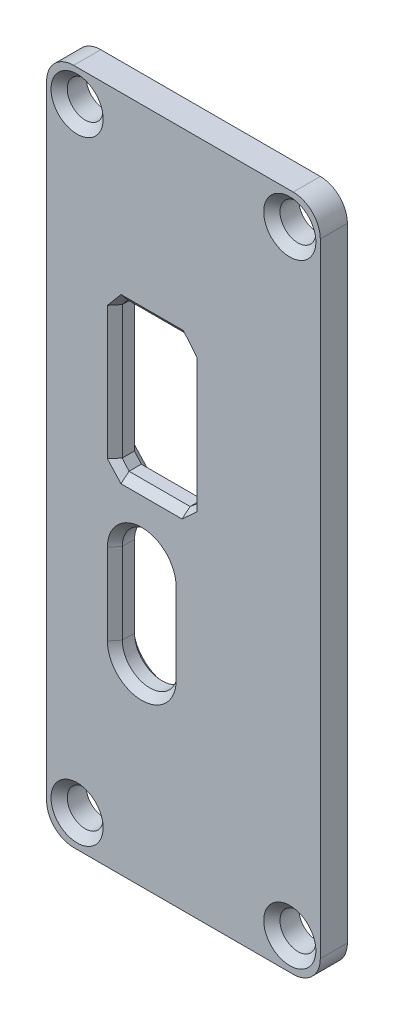
SolidWorks part; units mm, degrees
ref_plane "前视基准面" through (0, 0, 0) normal (0, 0, 1) x (1, 0, 0)
ref_plane "上视基准面" through (0, 0, 0) normal (0, 1, 0) x (1, 0, 0)
ref_plane "右视基准面" through (0, 0, 0) normal (1, 0, 0) x (0, 0, -1)
sketch "草图2" plane through (0, 0, 0) normal (0, 0, 1) x (1, 0, 0)
  line L5 (-3.7, 25) -> (16.5, 25)
  line L6 (-3.7, 25) -> (-3.7, -25)
  line L7 (-3.7, -25) -> (16.5, -25)
  line L8 (16.5, 25) -> (16.5, -25)
  line L9 (0, -23.5) -> (1.51, -23.5) construction
  line L10 (0, -20.5) -> (0, 20.5) construction
  line L11 (3.325, -4.555) -> (3.325, -10.545) construction
  line L12 (3.475, -4.555) -> (3.175, -4.555) construction
  line L13 (3.675, -10.545) -> (2.975, -10.545) construction
  line L14 (5.3615, -4.555) -> (5.3615, -10.545)
  line L15 (1.2885, -4.555) -> (1.2885, -10.545)
  line L16 (1.695, 10.95) -> (6.095, 10.95) construction
  line L17 (1.2885, 0.5) -> (6.8885, 0.5)
  line L18 (1.2885, 0.5) -> (1.2885, 11.5)
  line L19 (1.2885, 11.5) -> (6.8885, 11.5)
  line L20 (6.8885, 0.5) -> (6.8885, 11.5)
  arc A0 (5.3615, -4.555) -> (1.2885, -4.555) centre (3.325, -4.555) ccw
  arc A1 (1.2885, -10.545) -> (5.3615, -10.545) centre (3.325, -10.545) ccw
  circle A2 centre (-1.45, -22.65) radius 1.325
  circle A3 centre (-1.45, 22.65) radius 1.325
  circle A4 centre (14.25, 22.65) radius 1.325
  circle A5 centre (14.25, -22.65) radius 1.325
  point P14 (3.325, -7.55)
  point P29 (-1.6612, 22.7688)
  point P32 (14.6972, 23.1711)
  point P35 (0, 0)
  point P36 (0, 0)
  point P37 (0, 0)
  point P38 (0, 0)
  dimension "D8" = 2.65
  dimension "D1" = 50
  dimension "D2" = 20.2
  dimension "D3" = 1.5
  dimension "D4" = 3.7
  dimension "D5" = 5.6
  dimension "D6" = 11
  dimension "D7" = 0.55
  dimension "D9" = 2.35
  dimension "D10" = 2.25
  dimension "D11" = 45.3
  dimension "D12" = 15.7
extrude "凸台-拉伸1" add sketch "草图2" along normal blind 2
fillet "圆角1" radius 2 4 edges at (-3.7, 25, 1) (-3.7, -25, 1) (16.5, -25, 1) (16.5, 25, 1)
chamfer "倒角1" distance 0.6 angle 45 4 edges at (-0.125, -22.65, 2) (-0.125, 22.65, 2) (15.575, -22.65, 2) (15.575, 22.65, 2)
chamfer "倒角2" distance 0.5 angle 50 20 edges at (3.325, -12.5815, 2) (1.2885, -7.55, 2) (3.325, -2.5185, 2) (5.3615, -7.55, 2) (3.325, -12.5815, 0) (1.2885, -7.55, 0) (3.325, -2.5185, 0) (5.3615, -7.55, 0) (6.8885, 6, 2) (6.8885, 6, 0) (6.8885, 0.5, 1) (4.0885, 0.5, 2) (4.0885, 0.5, 0) (1.2885, 0.5, 1) (1.2885, 6, 2) (1.2885, 6, 0) (1.2885, 11.5, 1) (4.0885, 11.5, 2) (6.8885, 11.5, 1) (4.0885, 11.5, 0)
